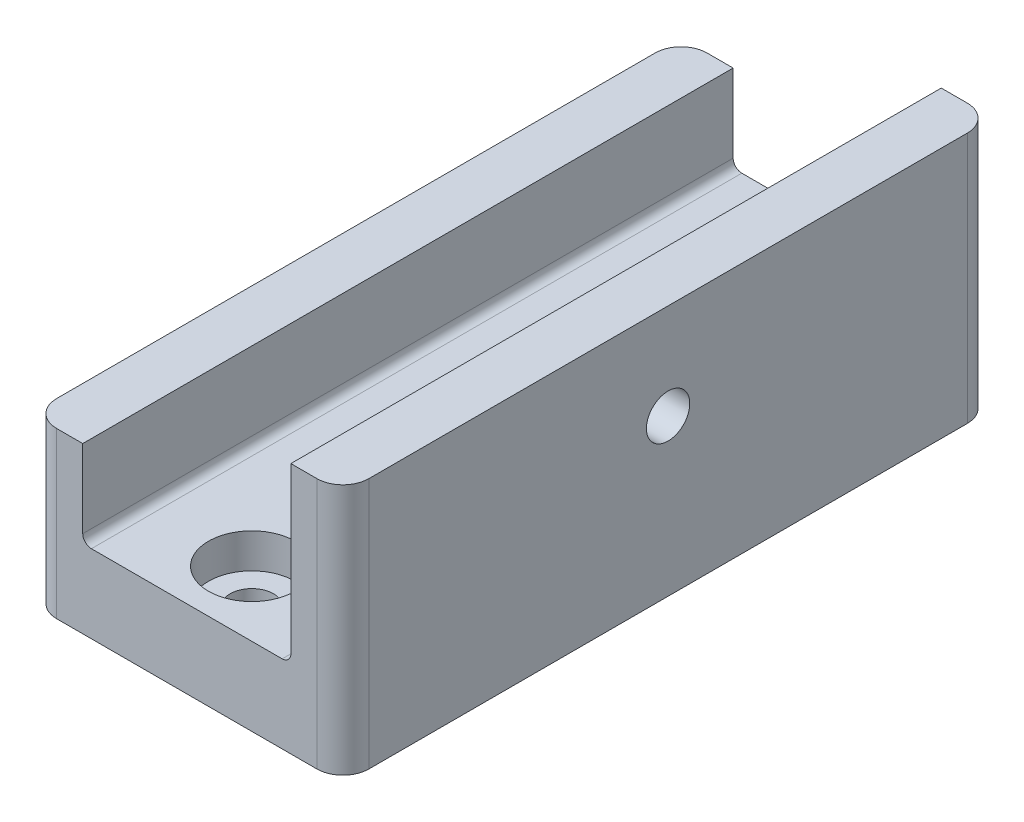
SolidWorks part; units mm, degrees
ref_plane "Front Plane" through (0, 0, 0) normal (0, 0, 1) x (1, 0, 0)
ref_plane "Top Plane" through (0, 0, 0) normal (0, 1, 0) x (1, 0, 0)
ref_plane "Right Plane" through (0, 0, 0) normal (1, 0, 0) x (0, 0, -1)
sketch "Sketch1" plane through (0, 0, 0) normal (0, 0, 1) x (1, 0, 0)
  line L0 (0, -55) -> (0, 55) construction
  line L1 (12, -4.5) -> (-12, -4.5)
  line L2 (12, -4.5) -> (12, 4.5)
  line L3 (12, 4.5) -> (-12, 4.5)
  line L4 (-12, -4.5) -> (-12, 4.5)
  line L5 (12, -4.5) -> (-12, 4.5) construction
  line L6 (12, 4.5) -> (-12, -4.5) construction
  line L7 (-12, -4.5) -> (-18, -4.5)
  line L8 (-12, -4.5) -> (-12, 14.5)
  line L9 (-12, 14.5) -> (-18, 14.5)
  line L10 (-18, -4.5) -> (-18, 14.5)
  line L15 (12, -4.5) -> (12, 4.5)
  line L17 (12, -4.5) -> (18, -4.5)
  line L18 (12, -4.5) -> (12, 24.5)
  line L19 (12, 24.5) -> (18, 24.5)
  line L20 (18, -4.5) -> (18, 24.5)
  point P0 (0, 0)
  dimension "D1" = 24
  dimension "D2" = 6
  dimension "D3" = 9
  dimension "D4" = 19
  dimension "D5" = 6
  dimension "D6" = 29
extrude "Boss-Extrude1" add sketch "Sketch1" along normal blind 75 contours L10 L7 L4 L8 L9 | L4 L1 L2 L3 | L17 L20 L19 L18 L2
fillet "Fillet1" radius 1 2 edges at (12, 4.5, 37.5) (-12, 4.5, 37.5)
fillet "Fillet2" radius 3 4 edges at (18, 10, 0) (18, 10, 75) (-18, 5, 0) (-18, 5, 75)
sketch "Sketch2" plane through (12, 0, 0) normal (-1, 0, 0) x (0, 0, 1)
  circle A0 centre (37.5, 13.5) radius 2.5
extrude "Cut-Extrude1" cut sketch "Sketch2" against normal blind 6
sketch "Sketch3" plane through (0, 4.5, 0) normal (0, 1, 0) x (1, 0, 0)
  circle A0 centre (0, -37.5) radius 2.5
  circle A1 centre (0, -7.5) radius 2.5
  circle A2 centre (0, -67.5) radius 2.5
  dimension "D1" = 2
  dimension "D2" = 2
extrude "Cut-Extrude2" cut sketch "Sketch3" against normal blind 10
sketch "Sketch4" plane through (0, 4.5, 0) normal (0, 1, 0) x (1, 0, 0)
  circle A0 centre (0, -7.5) radius 5
  circle A1 centre (0, -37.5) radius 5
  circle A2 centre (0, -67.5) radius 5
extrude "Cut-Extrude3" cut sketch "Sketch4" against normal blind 4
